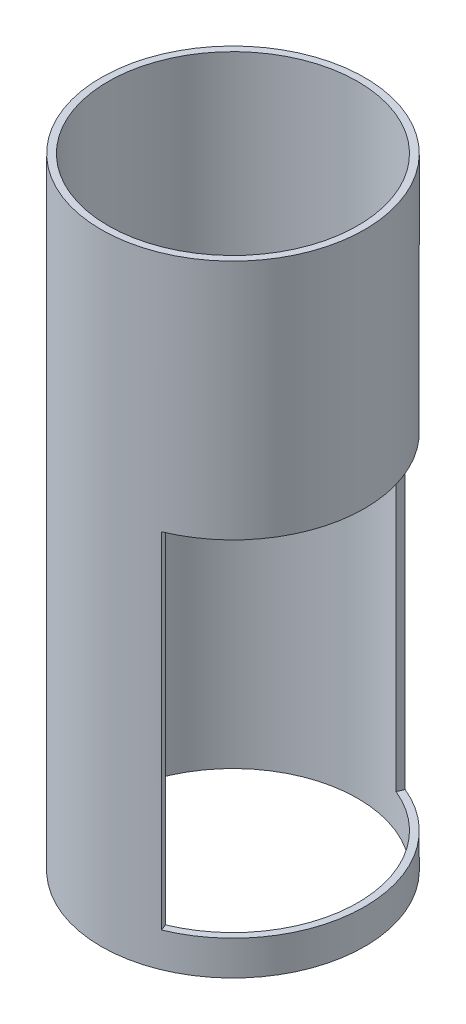
SolidWorks part; units mm, degrees
material "Custom Plastic"
ref_plane "Front Plane" through (0, 0, 0) normal (0, 0, 1) x (1, 0, 0)
ref_plane "Top Plane" through (0, 0, 0) normal (0, 1, 0) x (1, 0, 0)
ref_plane "Right Plane" through (0, 0, 0) normal (1, 0, 0) x (0, 0, -1)
sketch "Sketch1" plane through (0, 0, 0) normal (0, 1, 0) x (1, 0, 0)
  circle A0 centre (0, 0) radius 38.2
  dimension "D1" = 76.4
extrude "Boss-Extrude1" add sketch "Sketch1" along normal blind 180
shell "Shell1" thickness 2
ref_plane "Bottom Opening" through (0, 10, 0) normal (0, 1, 0) x (1, 0, 0)
sketch "Sketch4" plane through (0, 10, 0) normal (0, 1, 0) x (1, 0, 0)
  line L0 (0, 0) -> (14.6185, 35.2922)
  line L2 (0, 0) -> (14.6185, -35.2922)
  line L3 (-19.3893, 0) -> (-8.9043, 0) construction
  circle A2 centre (0, 0) radius 38.2 construction
  arc A3 (14.6185, -35.2922) -> (14.6185, 35.2922) centre (0, 0) ccw
  circle A4 centre (0, 0) radius 38.2 construction
  dimension "D1" = 135
  dimension "D2" = 67.5
ref_plane "Top Opening" through (0, 110, 0) normal (0, 1, 0) x (1, 0, 0)
extrude "Cut-Extrude2" cut sketch "Sketch4" along normal up to surface (100 mm away)
sketch "Sketch6" plane through (0, 0, 0) normal (0, 1, 0) x (1, 0, 0)
  line L0 (-13.8531, 33.4444) -> (-13.8531, -33.4444)
  line L2 (13.8531, 33.4444) -> (-13.8531, 33.4444)
  line L3 (13.8531, -33.4444) -> (-13.8531, -33.4444)
  line L4 (-17.8531, 31.4914) -> (-17.8531, -31.4914)
  circle A0 centre (0, 0) radius 36.2 construction
  circle A3 centre (0, 0) radius 36.2 construction
  arc A5 (13.8531, 33.4444) -> (-17.8531, 31.4914) centre (0, 0) ccw
  arc A6 (-17.8531, -31.4914) -> (13.8531, -33.4444) centre (0, 0) ccw
  point P4 (-36.2, 0)
  dimension "D2" = 4
extrude "Boss-Extrude4" [suppressed] add sketch "Sketch6" along normal up to surface (110 mm away) contours L4 A6 L0 A5 | L2 A5 | L3 A6
sketch "Sketch7" [suppressed] plane through (-17.8531, 0, 0) normal (-1, 0, 0) x (0, 0, 1)
  line L0 (-16, 80) -> (16, 80) construction
  circle A0 centre (-16, 80) radius 2
  circle A1 centre (16, 80) radius 2
  point P4 (0, 80)
  dimension "D1" = 4
  dimension "D2" = 4
  dimension "D3" = 32
  dimension "D4" = 80
extrude "Boss-Extrude5" [suppressed] add sketch "Sketch7" along normal blind 16
sketch "Sketch8" [suppressed] plane through (0, 180, 0) normal (0, 1, 0) x (1, 0, 0)
  line L0 (-33.8531, 18) -> (11.1469, 18) construction
  line L1 (-0.8531, 18) -> (-0.8531, -22.2698) construction
  line L2 (-0.8531, -22.2698) -> (-17.8531, -22.2698) construction
  point P3 (-0.8531, 18)
  dimension "D1" = 45
  dimension "D2" = 12
  dimension "D3" = 17
